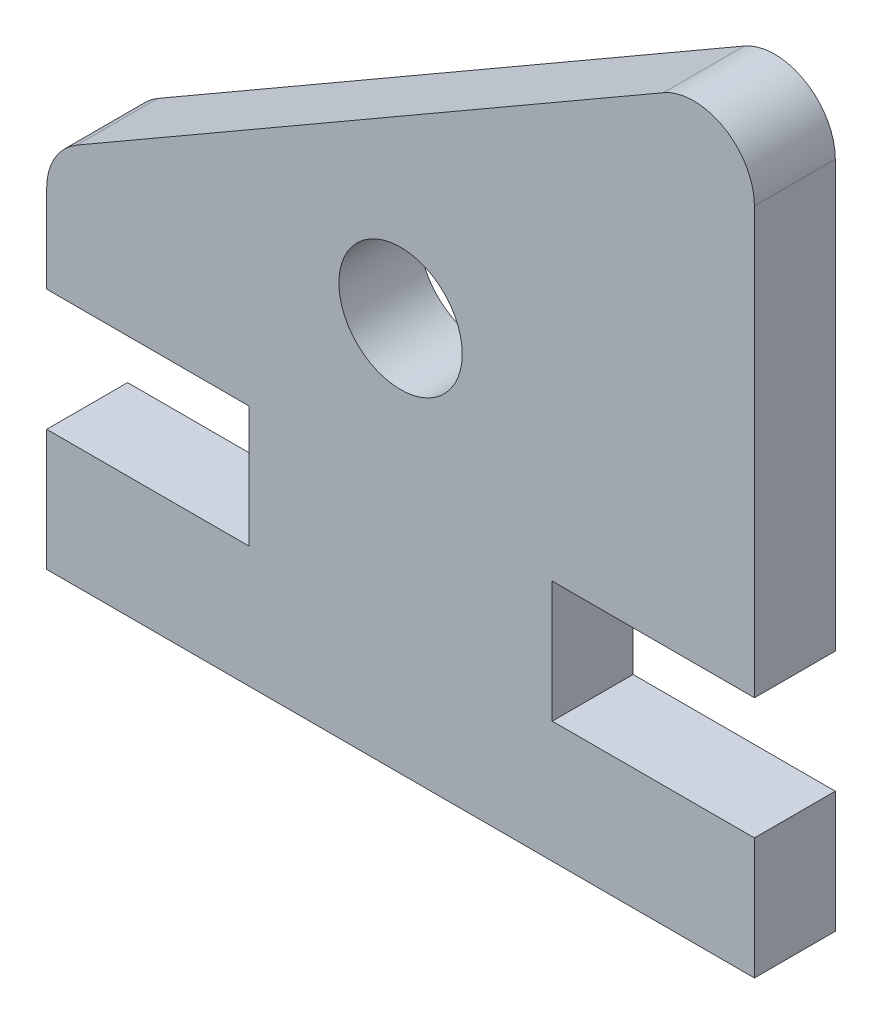
SolidWorks part; units mm, degrees
material "Policarbonato"
ref_plane "Plano frontal" through (0, 0, 0) normal (0, 0, 1) x (1, 0, 0)
ref_plane "Plano superior" through (0, 0, 0) normal (0, 1, 0) x (1, 0, 0)
ref_plane "Plano direito" through (0, 0, 0) normal (1, 0, 0) x (0, 0, -1)
sketch "Esboço1" plane through (0, 0, 0) normal (0, 0, 1) x (1, 0, 0)
  line L0 (-35, 18.0566) -> (0, 38.2639)
  line L1 (0, 38.2639) -> (0, 0)
  line L2 (0, 0) -> (-35, 0)
  line L3 (-35, 0) -> (-35, 18.0566)
  line L5 (-25, 6) -> (-35, 6)
  line L6 (-25, 6) -> (-25, 12)
  line L7 (-25, 12) -> (-35, 12)
  line L8 (-35, 6) -> (-35, 12)
  line L9 (-25, 6) -> (-35, 12) construction
  line L10 (-25, 12) -> (-35, 6) construction
  line L11 (0, 6) -> (-10, 6)
  line L12 (0, 6) -> (0, 12)
  line L13 (0, 12) -> (-10, 12)
  line L14 (-10, 6) -> (-10, 12)
  line L15 (0, 6) -> (-10, 12) construction
  line L16 (0, 12) -> (-10, 6) construction
  circle A0 centre (-17.5, 19.5) radius 3.05
  circle A1 centre (-17.5, 19.5) radius 7.5 construction
  point P2 (-5, 9)
  point P8 (-30, 9)
  point P19 (-17.5, 0)
  dimension "D10" = 6.1
  dimension "D11" = 15
  dimension "D1" = 30
  dimension "D3" = 35
  dimension "D5" = 10
  dimension "D6" = 6
  dimension "D9" = 6
extrude "Ressalto-extrusão1" add sketch "Esboço1" along normal blind 4 contours L11 L14 L13 L1 L0 L3 L7 L6 L5 L2 A0
fillet "Filete1" radius 3 2 edges at (-35, 18.0566, 2) (0, 38.2639, 2)
